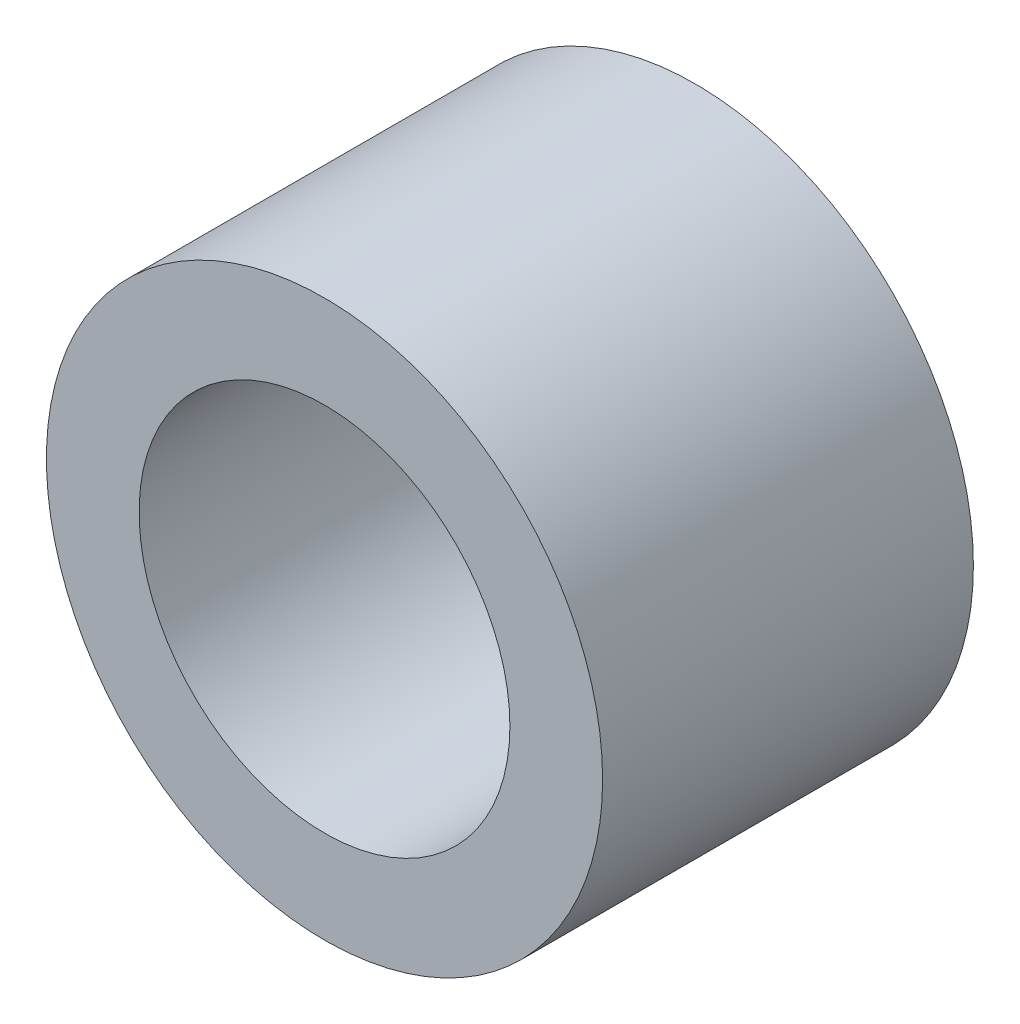
SolidWorks part; units mm, degrees
ref_plane "Спереди" through (0, 0, 0) normal (0, 0, 1) x (1, 0, 0)
ref_plane "Сверху" through (0, 0, 0) normal (0, 1, 0) x (1, 0, 0)
ref_plane "Справа" through (0, 0, 0) normal (1, 0, 0) x (0, 0, -1)
sketch "Эскиз1" plane through (0, 0, 0) normal (0, 0, 1) x (1, 0, 0)
  circle A0 centre (0, 0) radius 5
  circle A1 centre (0, 0) radius 7.5
  dimension "D1" = 10
  dimension "D2" = 15
extrude "Бобышка-Вытянуть1" add sketch "Эскиз1" along normal blind 10
